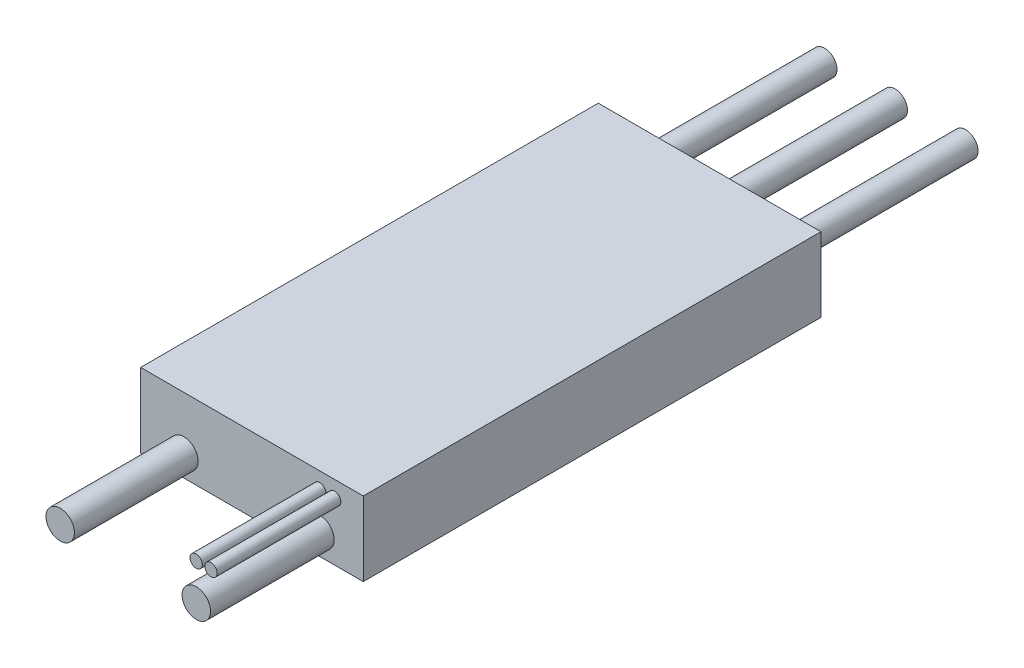
SolidWorks part; units mm, degrees
ref_plane "Plan de face" through (0, 0, 0) normal (0, 0, 1) x (1, 0, 0)
ref_plane "Plan de dessus" through (0, 0, 0) normal (0, 1, 0) x (1, 0, 0)
ref_plane "Plan de droite" through (0, 0, 0) normal (1, 0, 0) x (0, 0, -1)
sketch "Esquisse1" plane through (0, 0, 0) normal (0, 1, 0) x (1, 0, 0)
  line L1 (-9, 18.5) -> (9, 18.5)
  line L2 (-9, 18.5) -> (-9, -18.5)
  line L3 (-9, -18.5) -> (9, -18.5)
  line L4 (9, 18.5) -> (9, -18.5)
  point P4 (0, 18.5)
  point P6 (-9, 0)
  dimension "D1" = 18
  dimension "D2" = 37
extrude "Boss.-Extru.1" add sketch "Esquisse1" along normal blind 6
sketch "Esquisse2" plane through (0, 0, 18.5) normal (0, 0, 1) x (1, 0, 0)
  line L0 (0, 0) -> (0, 6) construction
  line L1 (-9, 6) -> (9, 6) construction
  circle A0 centre (-5.5, 1.7454) radius 1.15
  circle A2 centre (5.5, 1.7454) radius 1.15
  circle A3 centre (6.688, 4.6812) radius 0.5
  circle A4 centre (5.488, 4.6812) radius 0.5
  point P14 (-5.5, 1.7454)
  point P15 (6.347, 4.1993)
  point P16 (4.9078, 4.1993)
  point P17 (4.6925, 4.338)
  point P18 (6.688, 4.6812)
  dimension "D1" = 2.3
  dimension "D3" = 1
  dimension "D2" = 11
  dimension "D4" = 1.2
extrude "Boss.-Extru.2" add sketch "Esquisse2" along normal blind 10 separate body
sketch "Esquisse3" plane through (0, 0, -18.5) normal (0, 0, -1) x (-1, 0, 0)
  line L0 (0, 0) -> (0, 6) construction
  line L1 (-9, 6) -> (9, 6) construction
  circle A0 centre (-5.7, 3) radius 1
  circle A1 centre (0, 3) radius 1
  circle A2 centre (5.7, 3) radius 1
  point P7 (0, 3)
  dimension "D2" = 2
  dimension "D1" = 11.4
extrude "Boss.-Extru.3" add sketch "Esquisse3" along normal blind 15 separate body
